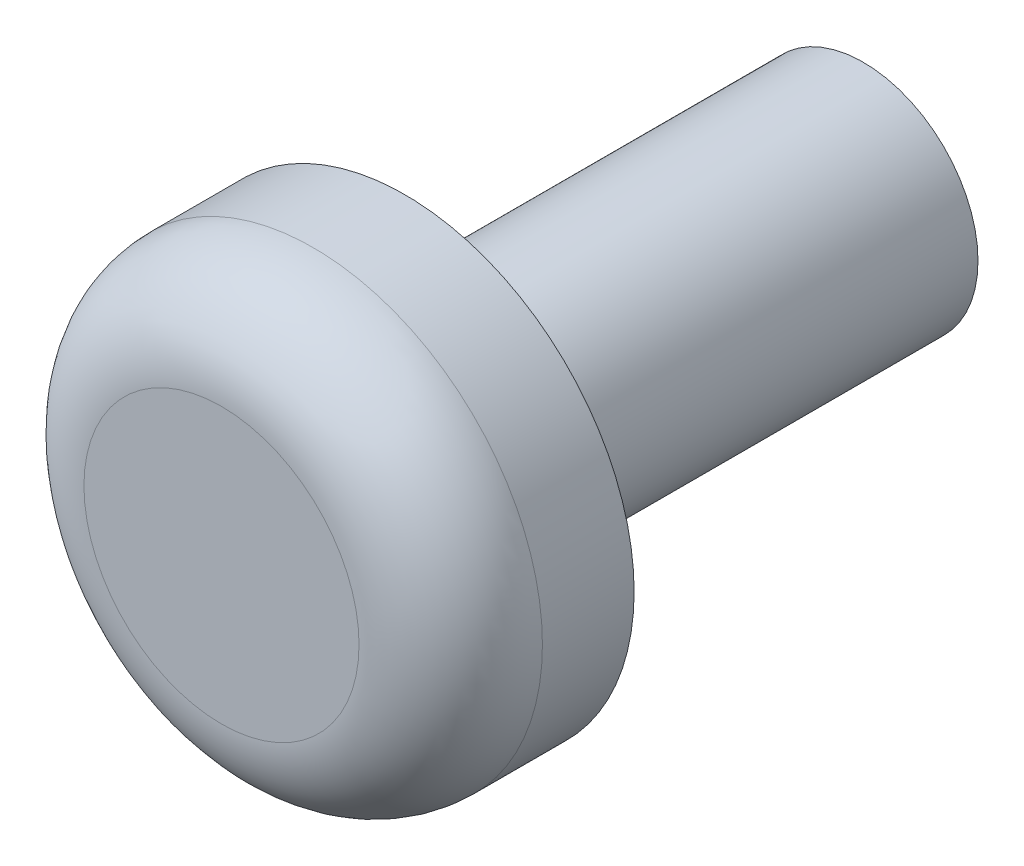
SolidWorks part; units mm, degrees
material "AISI 1045 Steel, cold drawn"
ref_plane "Front Plane" through (0, 0, 0) normal (0, 0, 1) x (1, 0, 0)
ref_plane "Top Plane" through (0, 0, 0) normal (0, 1, 0) x (1, 0, 0)
ref_plane "Right Plane" through (0, 0, 0) normal (1, 0, 0) x (0, 0, -1)
sketch "Sketch1" plane through (0, 0, 0) normal (0, 0, 1) x (1, 0, 0)
  circle A0 centre (0, 0) radius 1.25
  dimension "D1" = 2.5
extrude "Boss-Extrude1" add sketch "Sketch1" along normal blind 5
sketch "Sketch2" plane through (0, 0, 5) normal (0, 0, 1) x (1, 0, 0)
  circle A0 centre (0, 0) radius 2.5
extrude "Boss-Extrude2" add sketch "Sketch2" along normal blind 2
fillet "Fillet1" radius 1 1 edges at (2.5, 0, 7)
